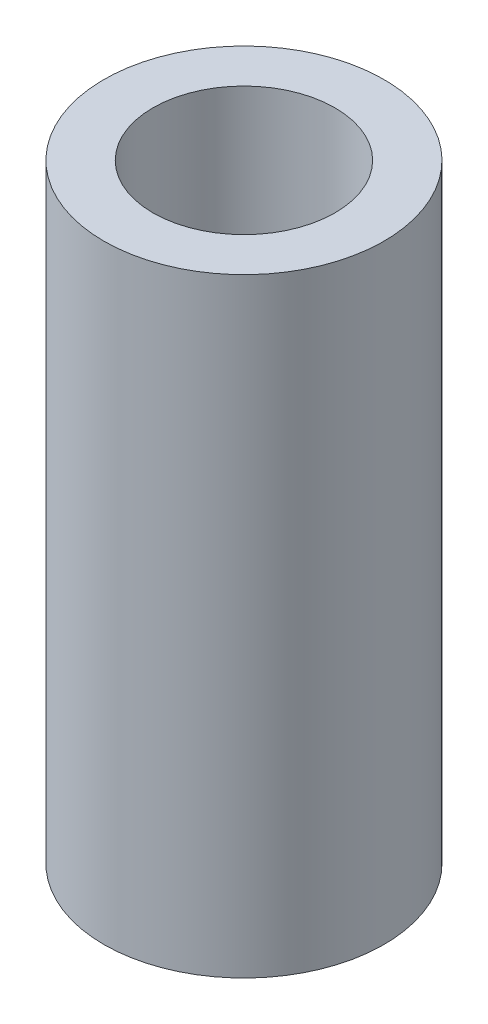
SolidWorks part; units mm, degrees
ref_plane "Front Plane" through (0, 0, 0) normal (0, 0, 1) x (1, 0, 0)
ref_plane "Top Plane" through (0, 0, 0) normal (0, 1, 0) x (1, 0, 0)
ref_plane "Right Plane" through (0, 0, 0) normal (1, 0, 0) x (0, 0, -1)
sketch "Sketch1" plane through (0, 0, 0) normal (0, 1, 0) x (1, 0, 0)
  circle A0 centre (0, 0) radius 2.54
  circle A1 centre (0, 0) radius 1.651
  dimension "D1" = 3.302
  dimension "D2" = 5.08
extrude "Boss-Extrude1" add sketch "Sketch1" along normal blind 11.049
